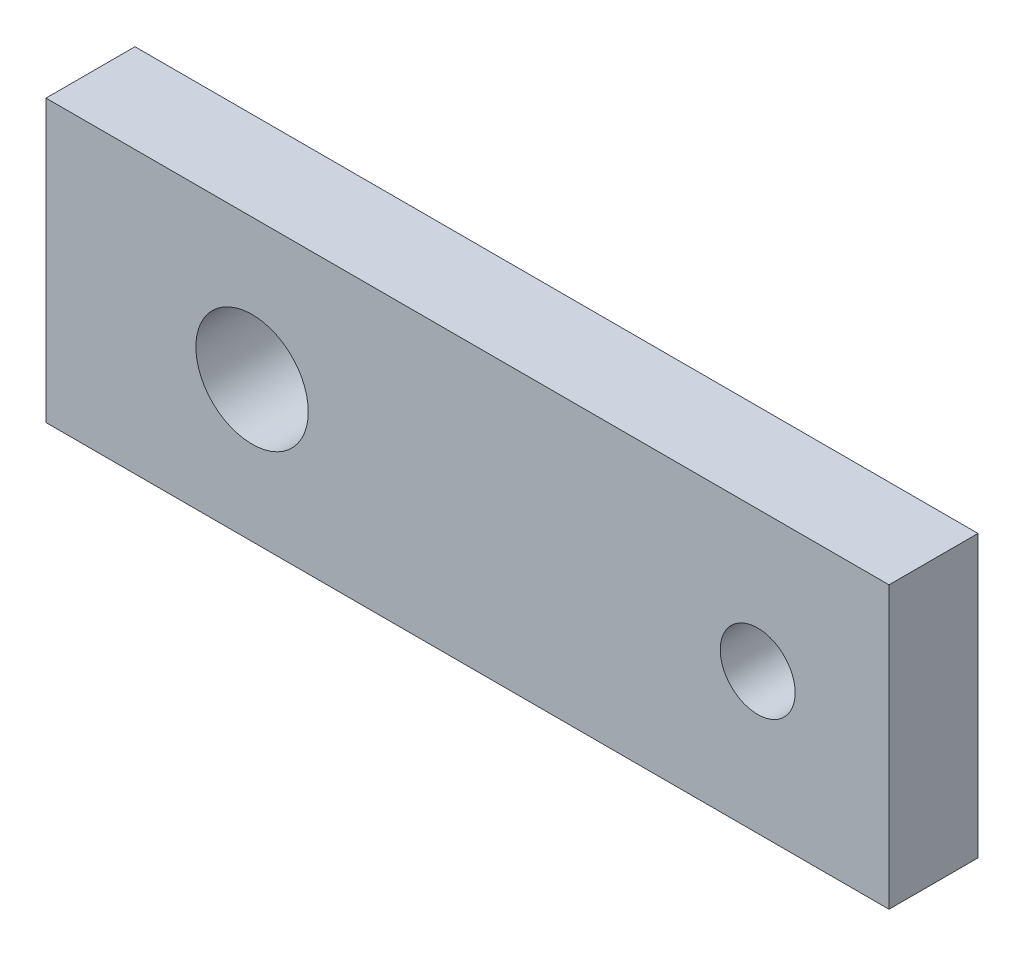
SolidWorks part; units mm, degrees
ref_plane "Ön Düzlem" through (0, 0, 0) normal (0, 0, 1) x (1, 0, 0)
ref_plane "Üst Düzlem" through (0, 0, 0) normal (0, 1, 0) x (1, 0, 0)
ref_plane "Sağ Düzlem" through (0, 0, 0) normal (1, 0, 0) x (0, 0, -1)
sketch "Sketch1" plane through (0, 0, 0) normal (0, 0, 1) x (1, 0, 0)
  line L0 (-23, 0) -> (30.98, 0) construction
  line L1 (-45, -15) -> (45, -15)
  line L2 (-45, -15) -> (-45, 15)
  line L3 (-45, 15) -> (45, 15)
  line L4 (45, -15) -> (45, 15)
  line L5 (-45, -15) -> (45, 15) construction
  line L6 (-45, 15) -> (45, -15) construction
  circle A0 centre (-23, 0) radius 6
  circle A1 centre (30.98, 0) radius 4
  point P0 (0, 0)
  dimension "D3" = 12
  dimension "D4" = 8
  dimension "D1" = 30
  dimension "D2" = 53.98
  dimension "D5" = 22
  dimension "D6" = 15
  dimension "D7" = 90
extrude "Boss-Extrude1" add sketch "Sketch1" along normal blind 9.5
sketch "Sketch2" plane through (0, -15, 0) normal (0, -1, 0) x (1, 0, 0)
  line L0 (45, 9.5) -> (45, 0) construction
  line L1 (-45, 0) -> (45, 0) construction
  line L2 (-45, 9.5) -> (-45, 0) construction
  circle A0 centre (7, 5) radius 2.5
  circle A1 centre (-37, 5) radius 2.5
  dimension "D5" = 5
  dimension "D1" = 38
  dimension "D2" = 8
  dimension "D3" = 5
  dimension "D4" = 5
extrude "Cut-Extrude1" cut sketch "Sketch2" against normal blind 15
